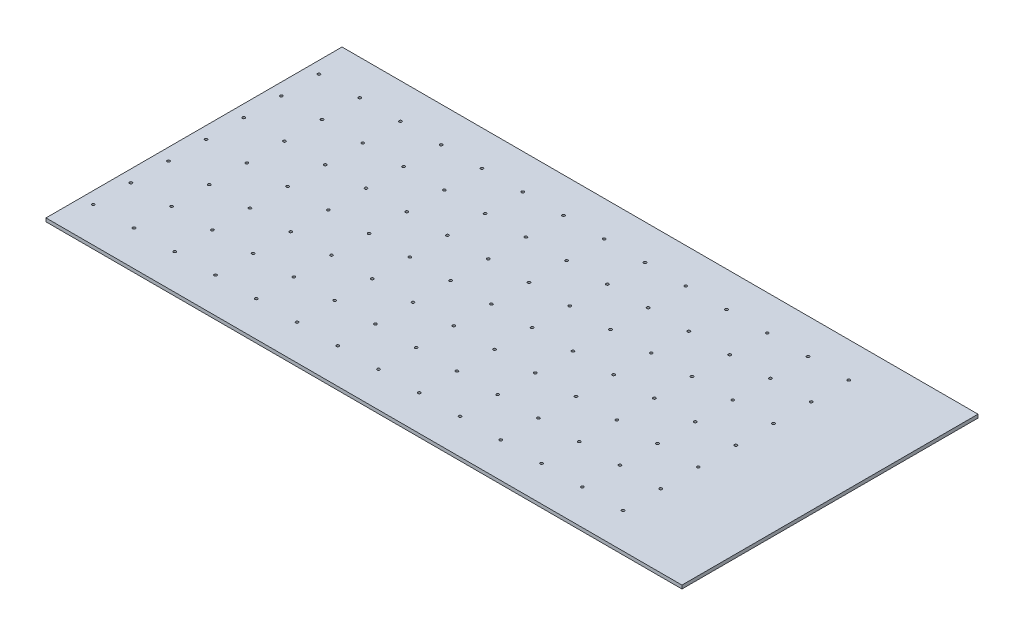
SolidWorks part; units mm, degrees
material "ABS PC"
ref_plane "Front Plane" through (0, 0, 0) normal (0, 0, 1) x (1, 0, 0)
ref_plane "Top Plane" through (0, 0, 0) normal (0, 1, 0) x (1, 0, 0)
ref_plane "Right Plane" through (0, 0, 0) normal (1, 0, 0) x (0, 0, -1)
sketch "Sketch1" plane through (0, 0, 0) normal (0, 1, 0) x (1, 0, 0)
  line L1 (-270, 129.32) -> (270, 129.32)
  line L2 (-270, 129.32) -> (-270, -129.32)
  line L3 (-270, -129.32) -> (270, -129.32)
  line L4 (270, 129.32) -> (270, -129.32)
  line L5 (-270, 129.32) -> (270, -129.32) construction
  line L6 (-270, -129.32) -> (270, 129.32) construction
  point P0 (0, 0)
  dimension "D1" = 540
  dimension "D2" = 258.64
extrude "Boss-Extrude1" add sketch "Sketch1" along normal blind 3.18
sketch "Sketch2" plane through (0, 3.18, 0) normal (0, 1, 0) x (1, 0, 0)
  line L0 (-270, 129.32) -> (-270, -129.32) construction
  line L1 (270, 129.32) -> (-270, 129.32) construction
  circle A0 centre (-258.82, 104.72) radius 1.25
  dimension "D1" = 2.5
  dimension "D2" = 11.18
  dimension "D3" = 24.6
extrude "Cut-Extrude1" cut sketch "Sketch2" against normal up to next
pattern_linear "LPattern1" count 14 spacing 37.81 along (1, 0, 0) count 7 spacing 34.9 along (0, 0, 1) of "Cut-Extrude1"
sketch "Sketch3" plane through (270, 0, 0) normal (1, 0, 0) x (0, 0, -1)
  line L1 (-129.32, 3.18) -> (129.32, 3.18)
  line L2 (-129.32, 3.18) -> (-129.32, 0)
  line L3 (-129.32, 0) -> (129.32, 0)
  line L4 (129.32, 3.18) -> (129.32, 0)
extrude "Boss-Extrude2" add sketch "Sketch3" along normal blind 50
sketch "Sketch4" plane through (0, 0, 129.32) normal (0, 0, 1) x (1, 0, 0)
  line L1 (320, 3.18) -> (-270, 3.18)
  line L2 (320, 3.18) -> (320, 0)
  line L3 (320, 0) -> (-270, 0)
  line L4 (-270, 3.18) -> (-270, 0)
extrude "Boss-Extrude3" add sketch "Sketch4" along normal blind 8
mirror "Mirror1" about plane through (0, 0, 0) normal (0, 0, 1) of "Boss-Extrude3"
